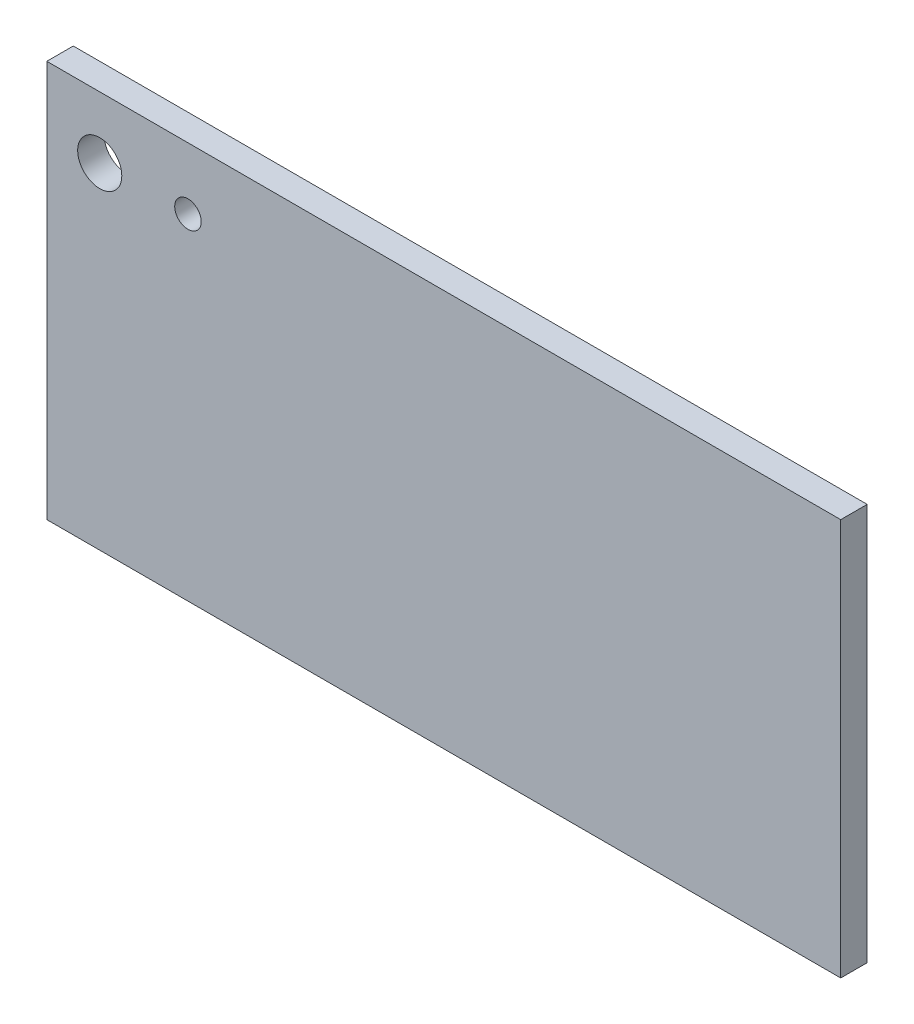
SolidWorks part; units mm, degrees
ref_plane "前基準面" through (0, 0, 0) normal (0, 0, 1) x (1, 0, 0)
ref_plane "上基準面" through (0, 0, 0) normal (0, 1, 0) x (1, 0, 0)
ref_plane "右基準面" through (0, 0, 0) normal (1, 0, 0) x (0, 0, -1)
sketch "草圖1" plane through (0, 0, 0) normal (0, 0, 1) x (1, 0, 0)
  line L1 (0, 0) -> (90, 0)
  line L2 (0, 0) -> (0, 45)
  line L3 (0, 45) -> (90, 45)
  line L4 (90, 0) -> (90, 45)
  dimension "D1" = 45
  dimension "D2" = 90
extrude "伸長1" add sketch "草圖1" along normal blind 3
sketch "草圖2" plane through (0, 0, 3) normal (0, 0, 1) x (1, 0, 0)
  line L0 (0, 45) -> (0, 0) construction
  line L1 (0, 0) -> (90, 0) construction
  circle A0 centre (6, 38) radius 2.5
  dimension "D1" = 5
  dimension "D4" = 38
  dimension "D3" = 6
extrude "Dia 5" cut sketch "草圖2" against normal through all
sketch "草圖3" plane through (0, 0, 3) normal (0, 0, 1) x (1, 0, 0)
  line L0 (0, 45) -> (0, 0) construction
  line L1 (16, 38) -> (6, 38) construction
  circle A0 centre (16, 38) radius 1.5
  dimension "D1" = 3
  dimension "D2" = 16
extrude "Dia 3" cut sketch "草圖3" against normal through all
